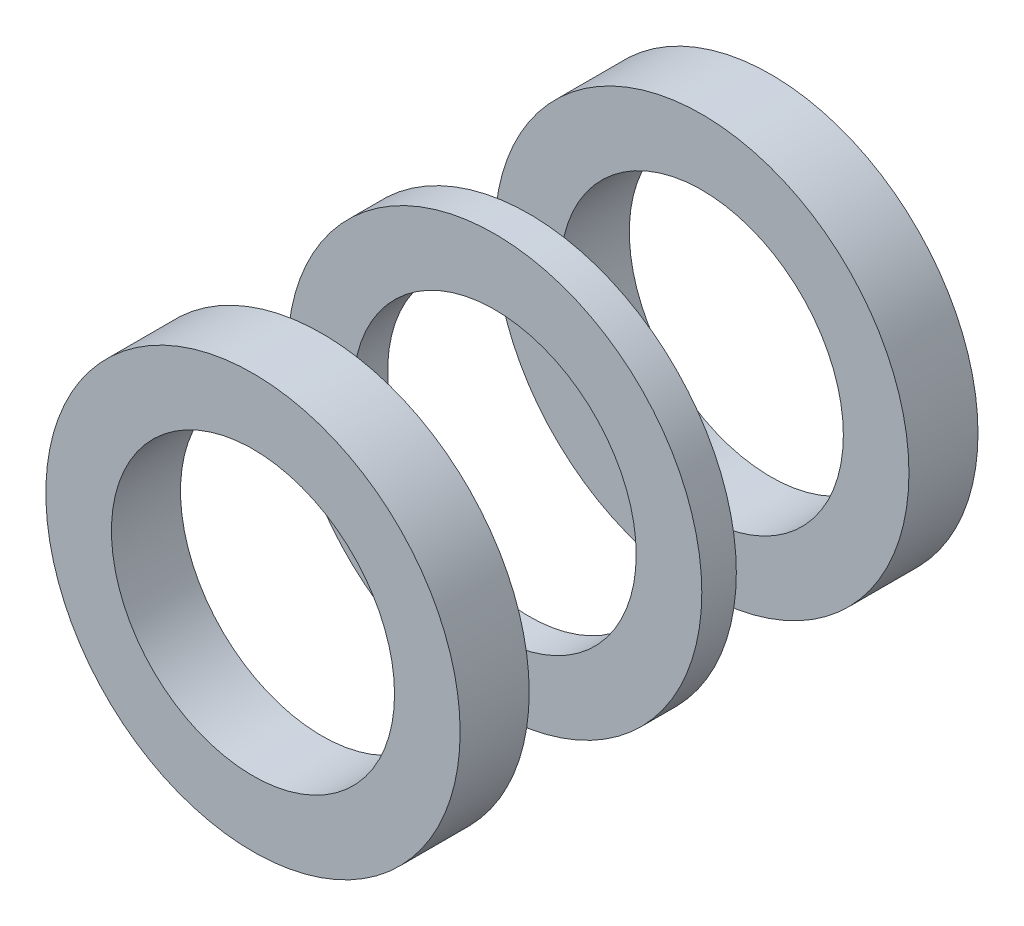
SolidWorks part; units mm, degrees
ref_plane "Спереди" through (0, 0, 0) normal (0, 0, 1) x (1, 0, 0)
ref_plane "Сверху" through (0, 0, 0) normal (0, 1, 0) x (1, 0, 0)
ref_plane "Справа" through (0, 0, 0) normal (1, 0, 0) x (0, 0, -1)
sketch "Эскиз1" plane through (0, 0, 0) normal (0, 0, 1) x (1, 0, 0)
  circle A0 centre (0, 0) radius 6
  circle A1 centre (0, 0) radius 4.1
extrude "Rear" add sketch "Эскиз1" along normal blind 2 from offset 29.5 separate body
sketch "Эскиз2" plane through (0, 0, 0) normal (0, 0, 1) x (1, 0, 0)
  circle A0 centre (0, 0) radius 6
  circle A1 centre (0, 0) radius 4.1
extrude "Middle" add sketch "Эскиз2" along normal blind 1 from offset 36.5 separate body
sketch "Эскиз3" plane through (0, 0, 0) normal (0, 0, 1) x (1, 0, 0)
  circle A0 centre (0, 0) radius 6
  circle A1 centre (0, 0) radius 4.1
extrude "Front" add sketch "Эскиз3" along normal blind 2 from offset 42.5 separate body
